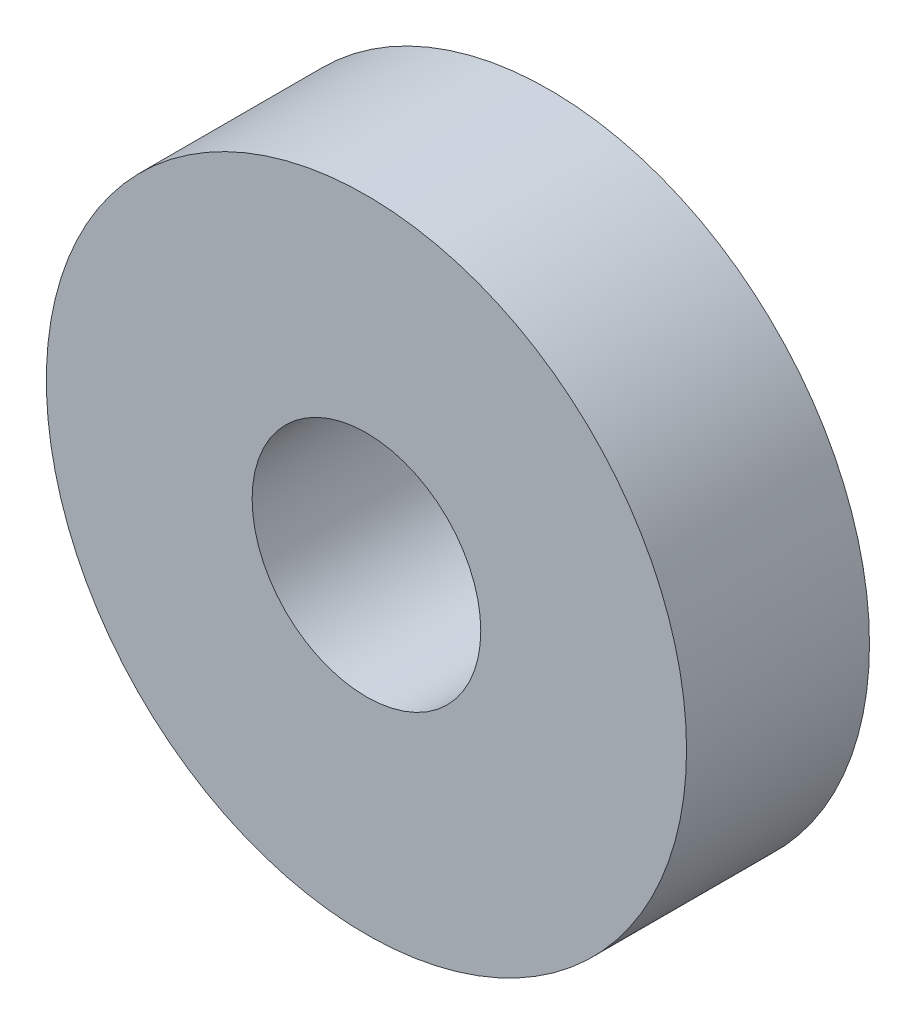
SolidWorks part; units mm, degrees
ref_plane "前基準面" through (0, 0, 0) normal (0, 0, 1) x (1, 0, 0)
ref_plane "上基準面" through (0, 0, 0) normal (0, 1, 0) x (1, 0, 0)
ref_plane "右基準面" through (0, 0, 0) normal (1, 0, 0) x (0, 0, -1)
sketch "草圖1" plane through (0, 0, 0) normal (0, 0, 1) x (1, 0, 0)
  circle A0 centre (0, 0) radius 7
extrude "填料-伸長1" add sketch "草圖1" along normal blind 4
sketch "草圖2" plane through (0, 0, 4) normal (0, 0, 1) x (1, 0, 0)
  circle A0 centre (0, 0) radius 2.5
extrude "除料-伸長1" cut sketch "草圖2" against normal blind 4
